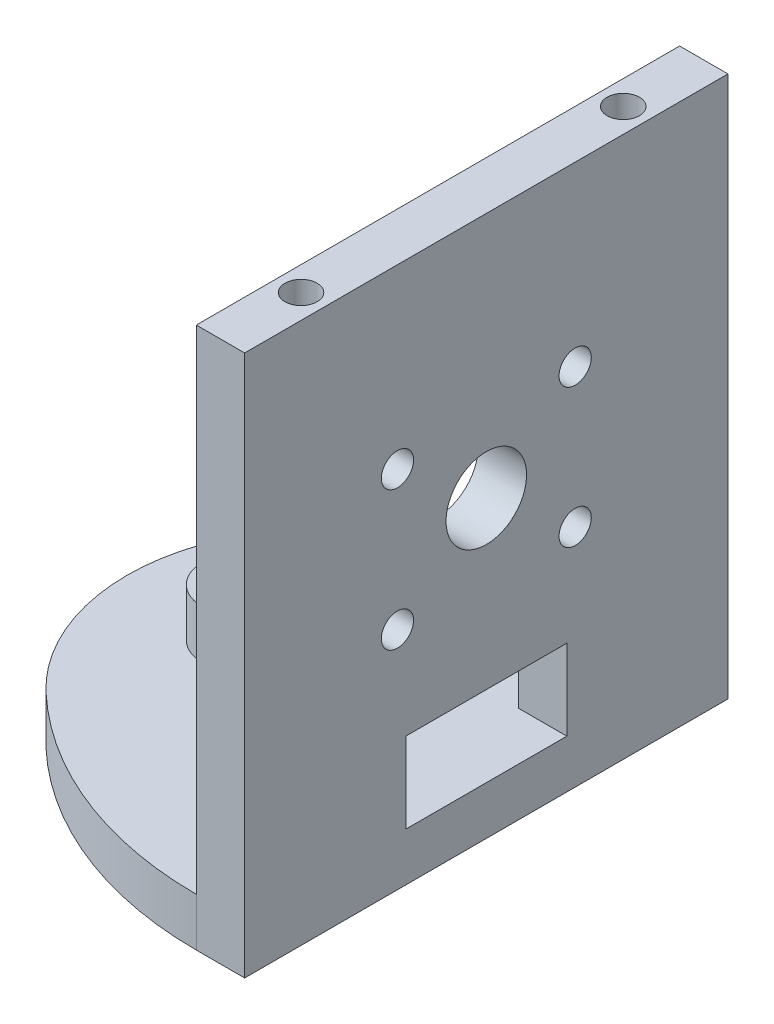
SolidWorks part; units mm, degrees
material "ABS"
ref_plane "Front Plane" through (0, 0, 0) normal (0, 0, 1) x (1, 0, 0)
ref_plane "Top Plane" through (0, 0, 0) normal (0, 1, 0) x (1, 0, 0)
ref_plane "Right Plane" through (0, 0, 0) normal (1, 0, 0) x (0, 0, -1)
sketch "Sketch1" plane through (0, 0, 0) normal (0, 1, 0) x (1, 0, 0)
  line L0 (0, 0) -> (11.2501, 0) construction
  line L1 (-3.2, -8.8283) -> (-3.2, 8.8283) construction
  line L12 (-7, 15) -> (15.3, 15)
  line L13 (-7, 15) -> (-7, -15)
  line L14 (-7, -15) -> (15.3, -15)
  line L15 (15.3, 15) -> (15.3, -15)
  line L16 (12.3, -15) -> (15.3, -15) construction
  line L17 (15.3, 15) -> (12.3, 15)
  line L18 (15.3, 15) -> (15.3, -15)
  line L19 (15.3, -15) -> (12.3, -15)
  line L20 (12.3, 15) -> (12.3, -15)
  line L21 (13.8, -15) -> (13.8, 15) construction
  circle A13 centre (0, 0) radius 2.35 construction
  arc A16 (12.3, -15) -> (-3.2, -8.8283) centre (12.3, 7.5496) cw
  arc A17 (12.3, 15) -> (-3.2, 8.8283) centre (12.3, -7.5496) ccw
  arc A18 (-3.2, 8.8283) -> (-3.2, -8.8283) centre (5.1551, 0) ccw
  dimension "D4" = 30
  dimension "D3" = 17
  dimension "D2" = 4.7
  dimension "D10" = 22.3
  dimension "D11" = 7
  dimension "D12" = 3
extrude "Boss-Extrude1" add sketch "Sketch1" against normal blind 3
sketch "Esquisse1" plane through (0, 0, 0) normal (0, 1, 0) x (1, 0, 0)
  line L1 (15.3, 15) -> (12.3, 15)
  line L2 (15.3, 15) -> (15.3, -15)
  line L3 (15.3, -15) -> (12.3, -15)
  line L4 (12.3, 15) -> (12.3, -15)
extrude "Boss.-Extru.1" add sketch "Esquisse1" along normal blind 30.6
sketch "Esquisse2" plane through (0, 30.6, 0) normal (0, 1, 0) x (1, 0, 0)
  line L0 (13.8, -10) -> (13.8, 10) construction
  line L1 (14.3016, 0) -> (21.3682, 0) construction
  line L2 (12.3, -15) -> (15.3, -15) construction
  line L3 (15.3, 15) -> (12.3, 15) construction
  line L4 (12.3, 15) -> (12.3, -15) construction
  line L5 (15.3, -15) -> (15.3, 15) construction
  circle A2 centre (13.8, 10) radius 1
  circle A4 centre (13.8, -10) radius 1
  dimension "D1" = 2
  dimension "D2" = 2
  dimension "D3" = 20
extrude "Enlèv. mat.-Extru.1" cut sketch "Esquisse2" against normal blind 3
sketch "Esquisse3" plane through (0, 0, 0) normal (0, 1, 0) x (1, 0, 0)
  circle A0 centre (0, 0) radius 2.35 construction
  circle A1 centre (0, 0) radius 2.35
extrude "Boss.-Extru.2" add sketch "Esquisse3" along normal blind 3
sketch "Esquisse4" plane through (12.3, 0, 0) normal (-1, 0, 0) x (0, 0, 1)
  line L0 (-15, 15.3) -> (15, 15.3) construction
  line L1 (-15, 30.6) -> (-15, 0) construction
  line L2 (15, 30.6) -> (15, 0) construction
  line L3 (0, 0) -> (0, 30.6) construction
  line L4 (-15, 0) -> (15, 0) construction
  line L5 (-15, 30.6) -> (15, 30.6) construction
  circle A0 centre (0, 15.3) radius 2.5
  dimension "D1" = 5
extrude "Enlèv. mat.-Extru.2" cut sketch "Esquisse4" against normal through all
sketch "Esquisse5" plane through (15.3, 0, 0) normal (1, 0, 0) x (0, 0, -1)
  circle A1 centre (5.5165, 19.6091) radius 1
  circle A2 centre (5.5165, 19.6091) radius 1
  circle A3 centre (5.5156, 10.9898) radius 1
  circle A4 centre (5.5156, 10.9898) radius 1
  circle A5 centre (-5.5156, 19.6102) radius 1
  circle A6 centre (-5.5156, 19.6102) radius 1
  circle A7 centre (-5.5165, 10.9909) radius 1
  circle A8 centre (-5.5165, 10.9909) radius 1
  dimension "D1" = 0
  dimension "D2" = 0
  dimension "D3" = 0
  dimension "D4" = 0
extrude "Enlèv. mat.-Extru.3" cut sketch "Esquisse5" against normal blind 10
sketch "Sketch2" plane through (12.3, 0, 0) normal (-1, 0, 0) x (0, 0, 1)
  line L0 (-15, 0) -> (15, 0) construction
  line L1 (-5, 0) -> (5, 0)
  line L2 (-5, 0) -> (-5, 5)
  line L3 (-5, 5) -> (5, 5)
  line L4 (5, 0) -> (5, 5)
  line L5 (0, 30.6) -> (0, 0) construction
  line L6 (-15, 30.6) -> (15, 30.6) construction
  dimension "D1" = 10
  dimension "D2" = 5
extrude "Cut-Extrude1" cut sketch "Sketch2" against normal through all
